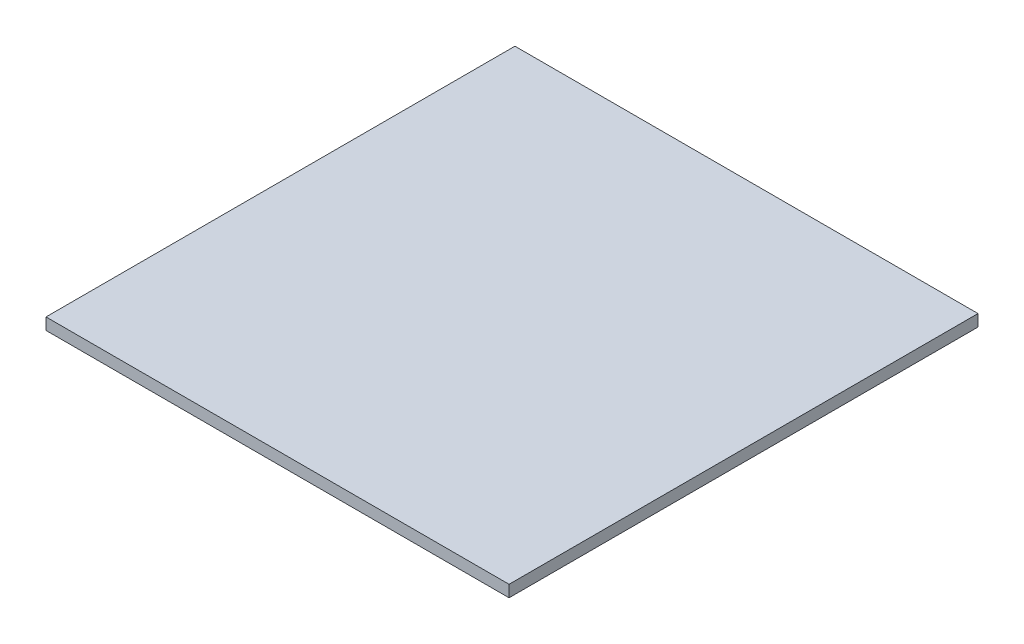
SolidWorks part; units mm, degrees
ref_plane "前视基准面" through (0, 0, 0) normal (0, 0, 1) x (1, 0, 0)
ref_plane "上视基准面" through (0, 0, 0) normal (0, 1, 0) x (1, 0, 0)
ref_plane "右视基准面" through (0, 0, 0) normal (1, 0, 0) x (0, 0, -1)
sketch "草图1" plane through (0, 0, 0) normal (0, 1, 0) x (1, 0, 0)
  line L1 (-79, 80) -> (79, 80)
  line L2 (-79, 80) -> (-79, -80)
  line L3 (-79, -80) -> (79, -80)
  line L4 (79, 80) -> (79, -80)
  line L5 (-79, 80) -> (79, -80) construction
  line L6 (-79, -80) -> (79, 80) construction
  point P0 (0, 0)
  dimension "D1" = 158
  dimension "D2" = 160
extrude "凸台-拉伸1" add sketch "草图1" along normal blind 4
